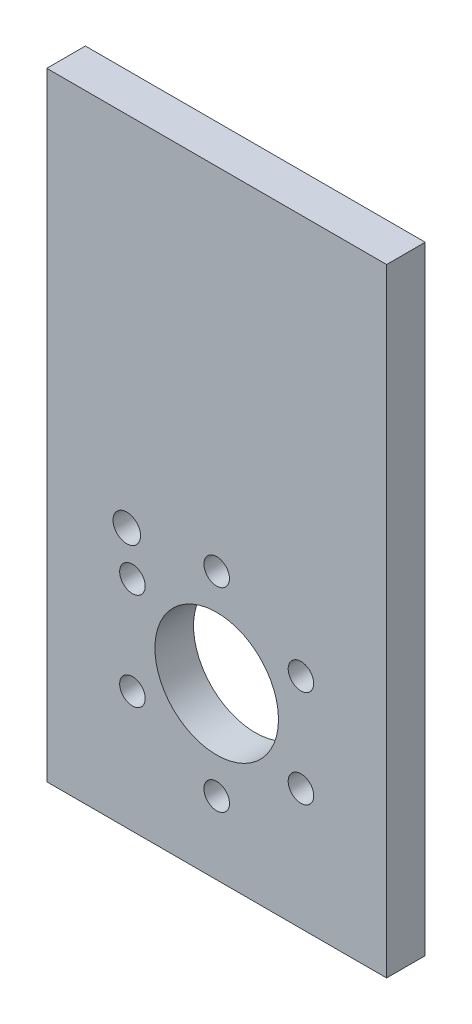
SolidWorks part; units mm, degrees
ref_plane "Front Plane" through (0, 0, 0) normal (0, 0, 1) x (1, 0, 0)
ref_plane "Top Plane" through (0, 0, 0) normal (0, 1, 0) x (1, 0, 0)
ref_plane "Right Plane" through (0, 0, 0) normal (1, 0, 0) x (0, 0, -1)
sketch "Model" plane through (0, 0, 0) normal (0, 0, 1) x (1, 0, 0)
  line L3 (-13.97, -13.97) -> (13.97, -13.97)
  line L4 (-13.97, -13.97) -> (-13.97, 36.83)
  line L5 (-13.97, 36.83) -> (13.97, 36.83)
  line L6 (13.97, -13.97) -> (13.97, 36.83)
  circle A0 centre (-6.9282, 4) radius 1.05
  circle A1 centre (-6.9282, -4) radius 1.05
  circle A2 centre (0, -8) radius 1.05
  circle A3 centre (6.9282, -4) radius 1.05
  circle A4 centre (6.9282, 4) radius 1.05
  circle A5 centre (0, 8) radius 1.05
  circle A6 centre (0, 0) radius 5.08
  circle A7 centre (0, 0) radius 17.907 construction
  dimension "D1" = 10.16
  dimension "D11" = 50.8
extrude "Boss-Extrude1" add sketch "Model" along normal blind 3.175
hole_wizard "#43 (0.089) Diameter Hole1" positions "Sketch3" profile "Sketch2" hole size "#43" standard "ANSI Inch"
sketch "Sketch3" plane through (0, 0, 3.175) normal (0, 0, 1) x (1, 0, 0)
  line L0 (13.97, -13.97) -> (13.97, 36.83) construction
  point P0 (-7.3914, 7.396)
  dimension "D1" = 21.3614
sketch "Sketch2" plane through (-7.3914, 7.396, 3.175) normal (1, 0, 0) x (0, -1, 0)
  line L0 (0, 0) -> (0, 26.0792)
  line L1 (0, 26.0792) -> (1.1303, 25.4)
  line L2 (1.1303, 25.4) -> (1.1303, 0)
  line L5 (1.1303, 0) -> (0, 0)
  line L10 (0, 26.0792) -> (-1.1303, 25.4) construction
  line L11 (0, -6.35) -> (0, 107.95) construction
  dimension "Hole Dia." = 2.2606
  dimension "Hole Depth" = 25.4
  dimension "Drill Angle" = 118
